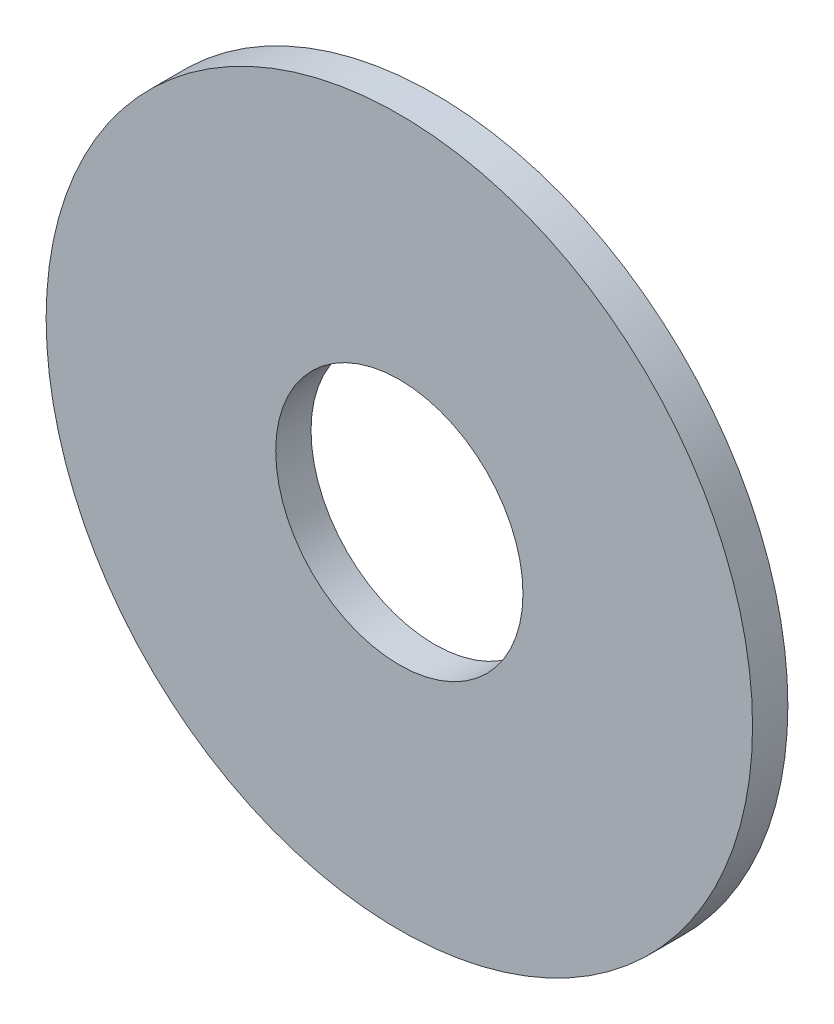
SolidWorks part; units mm, degrees
ref_plane "Спереди" through (0, 0, 0) normal (0, 0, 1) x (1, 0, 0)
ref_plane "Сверху" through (0, 0, 0) normal (0, 1, 0) x (1, 0, 0)
ref_plane "Справа" through (0, 0, 0) normal (1, 0, 0) x (0, 0, -1)
sketch "Эскиз1" plane through (0, 0, 0) normal (0, 0, 1) x (1, 0, 0)
  circle A0 centre (0, 0) radius 20
  circle A1 centre (0, 0) radius 7
  dimension "D1" = 40
  dimension "D2" = 14
extrude "Вытянуть1" add sketch "Эскиз1" along normal blind 2
